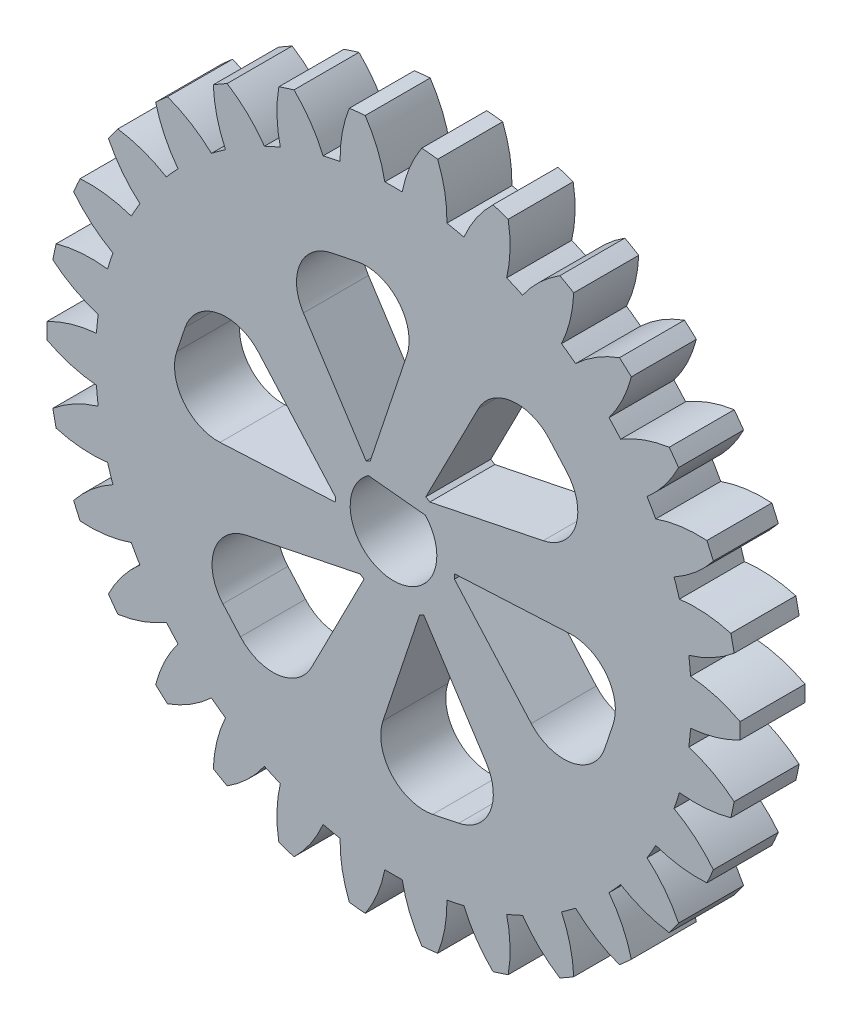
SolidWorks part; units mm, degrees
ref_plane "Front Plane" through (0, 0, 0) normal (0, 0, 1) x (1, 0, 0)
ref_plane "Top Plane" through (0, 0, 0) normal (0, 1, 0) x (1, 0, 0)
ref_plane "Right Plane" through (0, 0, 0) normal (1, 0, 0) x (0, 0, -1)
sketch "Sketch1" plane through (0, 0, 0) normal (0, 0, 1) x (1, 0, 0)
  circle A0 centre (0, 0) radius 16
extrude "Boss-Extrude1" add sketch "Sketch1" along normal blind 3
sketch "Sketch2" plane through (0, 0, 3) normal (0, 0, 1) x (1, 0, 0)
  line L0 (0, 0) -> (0, 27.5) construction
  line L1 (0, 0) -> (-3.3414, 31.7908) construction
  line L2 (-1.5658, 14.8971) -> (-0.7804, 14.9797) construction
  circle A0 centre (0, 0) radius 13.75 construction
  circle A1 centre (0, 0) radius 14.0954 construction
  circle A2 centre (0, 0) radius 15 construction
  circle A10 centre (0, 0) radius 16 construction
  arc A11 (-1.3054, 15.9467) -> (-0.4013, 13.7441) centre (-6.2936, 12.6123) cw
  arc A15 (1.3054, 15.9467) -> (0.4013, 13.7441) centre (6.2936, 12.6123) ccw
  arc A16 (1.3054, 15.9467) -> (-1.3054, 15.9467) centre (0, 0) ccw
  arc A17 (0.4013, 13.7441) -> (-0.4013, 13.7441) centre (0, 0) ccw
  circle A18 centre (0, 0) radius 16 construction
  point P10 (0, 13.75)
  dimension "D4" = 6
extrude "Cut-Extrude1" cut sketch "Sketch2" against normal blind 10
pattern_circular "CirPattern1" count 30 over 360 about axis through (0, 0, 0) along (0, 0, 1) of "Cut-Extrude1"
sketch "Sketch3" plane through (0, 0, 0) normal (0, 0, -1) x (-1, 0, 0)
  line L15 (1.0713, 2.2588) -> (1.2637, 2.1571)
  line L16 (1.0713, 2.2588) -> (-1.7124, 10.6127)
  line L17 (-1.7124, 10.6127) -> (5.7455, 9.0858)
  line L18 (5.7455, 9.0858) -> (1.2637, 2.1571)
  line L19 (1.1358, 1.4518) -> (1.0713, 1.5)
  line L20 (1.0713, 1.5) -> (-1.0713, 1.5)
  arc A0 (-1.0713, 1.5) -> (1.1358, 1.4518) centre (0, 0) ccw
  circle A1 centre (0, 0) radius 10.75
  arc A2 (0.4013, 13.7441) -> (-0.4013, 13.7441) centre (0, 0) ccw construction
  circle A3 centre (0, 0) radius 2.5
  dimension "D1" = 3
  dimension "D2" = 5
  dimension "D3" = 60
  dimension "D4" = 1.5
extrude "Cut-Extrude2" cut sketch "Sketch3" against normal blind 10 contours L18 L15 L16 L17
fillet "Fillet7" radius 2 1 edges at (1.7124, 10.6127, 1.5)
fillet "Fillet8" radius 2 1 edges at (-5.7455, 9.0858, 1.5)
pattern_circular "CirPattern4" count 6 over 360 about axis through (0.0656, -0.2564, 0) along (0, 0, 1) of "Cut-Extrude2", "Fillet7", "Fillet8"
sketch "Sketch4" plane through (0, 0, 0) normal (0, 0, -1) x (-1, 0, 0)
  line L1 (-1.4681, 1.3582) -> (1.164, 1.6264)
  arc A1 (-1.4681, 1.3582) -> (1.164, 1.6264) centre (0, 0) ccw
  dimension "D2" = 1.5
  dimension "D1" = 4
extrude "Cut-Extrude3" cut sketch "Sketch4" against normal blind 10
equation "\"module\"= 1.0"
equation "\"teeth\"= 30"
equation "\"pressureAngle\"= 20deg"
equation "\"gearThickness\"= 3"
equation "\"addendumFactor\"= 1"
equation "\"dedendumFactor\"= 1.25"
equation "\"pitch\"= 1 / \"module\""
equation "\"pitchDiameter\"= \"teeth\" / \"pitch\""
equation "\"addendum\"= \"addendumFactor\" / \"pitch\""
equation "\"dedendum\"= \"dedendumFactor\" / \"pitch\""
equation "\"addendumDiameter@Sketch1\" = \"pitchDiameter\" + 2 * \"addendum\""
equation "\"D1@Sketch2\"=\"pitchDiameter\"-2*\"dedendum\""
equation "\"D2@Sketch2\"=\"pitchDiameter\" * cos ( \"pressureAngle\" )"
equation "\"D3@Sketch2\"=\"pitchDiameter\""
equation "\"D4@Sketch2\"=180/\"teeth\""
equation "\"D5@Sketch2\"=\"pitchDiameter\"/5"
equation "\"D1@CirPattern1\"=\"teeth\""
equation "\"D6@Sketch2\"=PI/2/\"pitch\"/2"
